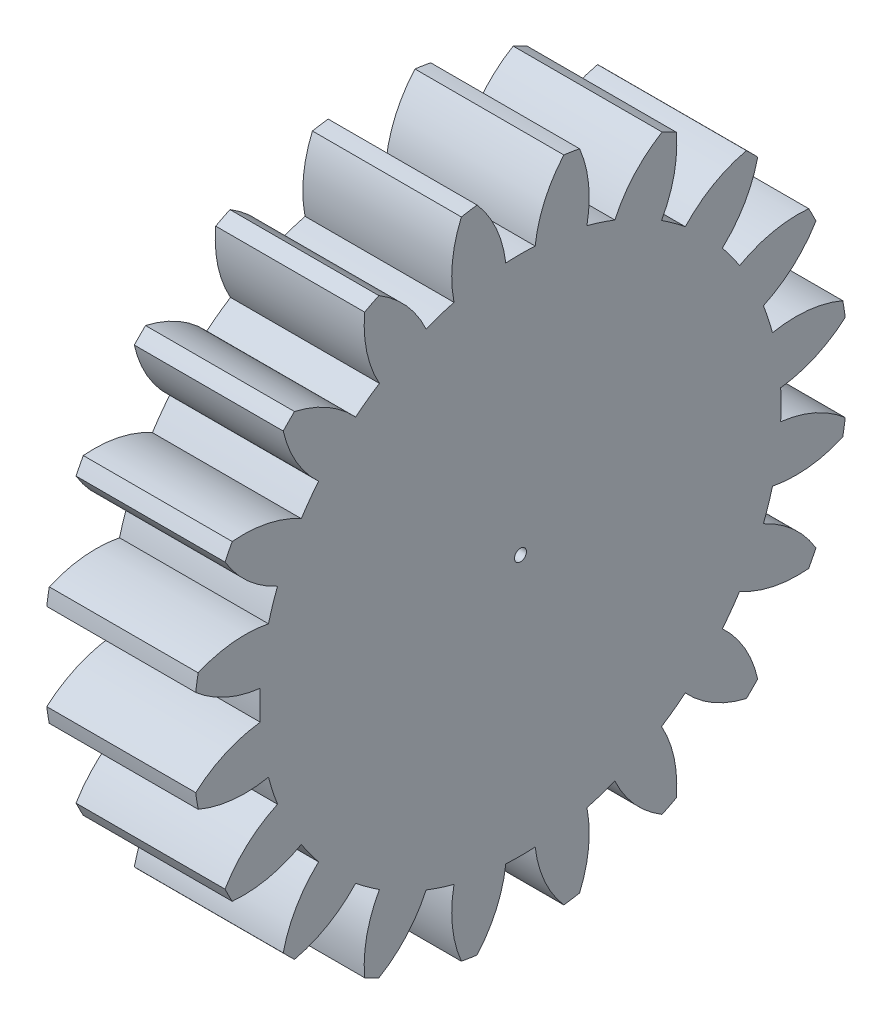
SolidWorks part; units mm, degrees
ref_plane "Plane1" through (0, 0, 0) normal (0, 0, 1) x (1, 0, 0)
ref_plane "Plane2" through (0, 0, 0) normal (0, 1, 0) x (1, 0, 0)
ref_plane "Plane3" through (0, 0, 0) normal (1, 0, 0) x (0, 0, -1)
sketch "HoldingSke" plane through (0, 0, 0) normal (0, 1, 0) x (1, 0, 0)
  line L0 (0, 0) -> (0.4698, -0.171)
  line L1 (-15, 0) -> (100, 0) construction
  line L2 (0, 0) -> (-2.1039, 2.3779)
  line L3 (0, 0) -> (-11.863, 4.5341)
  line L4 (0, 0) -> (8.1152, 2.9537)
  line L5 (0, 0) -> (-46.8476, -17.4728)
  line L6 (0, 0) -> (-9.9476, -6.7116)
  line L7 (-2.1039, 2.3779) -> (8.6586, 51.2059)
  line L8 (-76.2, 54.61) -> (-76.1, 54.61)
  line L9 (-71.009, 38.7566) -> (-53.1078, 45.2721)
  line L10 (-76.2, 71.12) -> (104.1128, 71.12)
  line L11 (0, 0) -> (-12, 0)
  line L12 (-76.2, 101.6) -> (-76.133, 101.6)
  line L13 (24.9733, 27.94) -> (52.9518, 28.4284)
  line L14 (24.9733, 27.94) -> (24.9743, 27.94)
  line L15 (24.9733, 27.94) -> (100.4006, 29.5858)
  line L16 (-63.627, -2) -> (-12.827, -2)
  circle A0 centre (0, 0) radius 0.4
  circle A1 centre (0, 0) radius 17.499
  circle A2 centre (0, 0) radius 37.5
  circle A3 centre (0, 0) radius 0.4
  dimension "MHD" = 34.998
  dimension "Hub_dia" = 75
  dimension "Bore" = 0.8
  dimension "MBD" = 0.8
  dimension "Num_teeth" = 20
  dimension "Pitch_radius" = 180.3128
  dimension "Pitch" = 0.5
  dimension "Width" = 12
  dimension "Overall_len" = 50
  dimension "Show_teeth" = 20
  dimension "Thickness" = 12
  dimension "OAL" = 50.0001
  dimension "T_dim" = 0.1
  dimension "Ap" = 20
  dimension "H" = 19.05
  dimension "Backlash" = 0.067
  dimension "Addendum_fac" = 1
  dimension "Dedendum_fac" = 1.25
  dimension "Clearance_fac" = 0.25
  dimension "Dedendum_add" = 0.001
  dimension "Module" = 2
sketch "BasProSke" plane through (0, 0, 0) normal (0, 1, 0) x (1, 0, 0)
  line L0 (-10, 0) -> (60, 0) construction
  line L1 (0, 0) -> (0, 22)
  line L2 (0, 0) -> (10, 0)
  line L3 (10, 0) -> (10, 22)
  line L4 (10, 22) -> (0, 22)
  dimension "Diameter" = 44
  dimension "Thickness" = 10
revolve "Base-Revolve" add sketch "BasProSke" angle 360 about L0
sketch "TooCutSke" plane through (0, 0, 0) normal (1, 0, 0) x (0, 0, -1)
  line L1 (0, 0) -> (0, 107) construction
  line L2 (0, 0) -> (-1.6864, 19.9288) construction
  line L3 (0, 0) -> (-6.2409, 39.4033) construction
  line L4 (-1.6864, 19.9288) -> (-3.1204, 19.7016) construction
  arc A0 (0.9862, 17.4712) -> (-0.9862, 17.4712) centre (0, 0) ccw
  arc A1 (2.9329, 21.8293) -> (-2.9329, 21.8293) centre (0, 0) ccw
  circle A2 centre (0, 0) radius 20 construction
  circle A3 centre (0, 0) radius 18.7939 construction
  arc A4 (-0.9862, 17.4712) -> (-2.9329, 21.8293) centre (-8.9313, 16.536) ccw
  arc A5 (2.9329, 21.8293) -> (0.9862, 17.4712) centre (8.9313, 16.536) ccw
  dimension "Root_dia" = 34.998
  dimension "Overcut_dia" = 44.0508
  dimension "Pitch_dia" = 40
  dimension "Base_dia" = 37.5877
  dimension "Flank_rad" = 8
  dimension "Half_ang" = 9
  dimension "Half_CT" = 1.4519
extrude "ToothCut" cut sketch "TooCutSke" along normal through all
fillet "Breaks" [suppressed] radius 0.04
fillet "RootFillets" [suppressed] radius 0.501
pattern_circular "TeethCuts" count 20 every 18 about axis through (-10, 0, 0) along (1, 0, 0) of "ToothCut", "RootFillets", "Breaks"
sketch "HubNeaOneSke" plane through (0, 0, 0) normal (-1, 0, 0) x (0, 0, 1)
  circle A0 centre (0, 0) radius 17.499
  dimension "Diameter" = 34.998
extrude "HubNearOne" [suppressed] add sketch "HubNeaOneSke" along normal blind 40.0001
sketch "HubNeaBotSke" plane through (0, 0, 0) normal (-1, 0, 0) x (0, 0, 1)
  circle A0 centre (0, 0) radius 17.499
  dimension "Diameter" = 34.998
extrude "HubNearBoth" [suppressed] add sketch "HubNeaBotSke" along normal blind 20
ref_plane "FarPln" through (10, 0, 0) normal (1, 0, 0) x (0, 0, -1)
sketch "HubFarSke" plane through (10, 0, 0) normal (1, 0, 0) x (0, 0, -1)
  circle A0 centre (0, 0) radius 17.499
  dimension "Diameter" = 34.998
extrude "HubFar" [suppressed] add sketch "HubFarSke" along normal blind 20
sketch "BorSke" plane through (0, 0, 0) normal (1, 0, 0) x (0, 0, -1)
  circle A0 centre (0, 0) radius 0.4
  dimension "Diameter" = 0.8
extrude "Bore" cut sketch "BorSke" along normal mid plane 100.0001
sketch "KeySke" plane through (0, 0, 0) normal (1, 0, 0) x (0, 0, -1)
  line L0 (-0.05, 0) -> (-0.05, 0.5)
  line L1 (-0.05, 0.5) -> (0.05, 0.5)
  line L2 (0.05, 0.5) -> (0.05, 0)
  line L3 (0, 0) -> (0, 34) construction
  line L4 (-0.05, 0) -> (0.05, 0)
  dimension "Offset" = 0.5
  dimension "Width" = 0.1
extrude "Keyway" [suppressed] cut sketch "KeySke" along normal mid plane 100.0001
pattern_circular "Keyway2" [suppressed] count 2 every 90 about axis through (-10, 0, 0) along (1, 0, 0)
equation "' \"Module@HoldingSke\" = 6.35"
equation "' \"Num_teeth@HoldingSke\" = 12"
equation "' \"Ap@HoldingSke\" =  20"
equation "' \"Width@HoldingSke\" = 0.5 * 25.4"
equation "' \"Hub_dia@HoldingSke\"= 1 * 25.4"
equation "' \"Overall_len@HoldingSke\" = 1.0 * 25.4"
equation "' \"Bore@HoldingSke\" = 0.75 * 25.4"
equation "' \"T_dim@HoldingSke\" = 0.1 * 25.4"
equation "' \"Width@KeySke\" = 0.25 * 25.4"
equation "' \"Show_teeth@HoldingSke\" = 13"
equation "' \"Backlash@HoldingSke\" = 0.009 * 25.4"
equation "' \"Addendum_fac@HoldingSke\" = 1.0"
equation "' \"Dedendum_fac@HoldingSke\" = 1.25"
equation "' \"Dedendum_add@HoldingSke\" = 0.00005 * 25.4"
equation "' \"Clearance_fac@HoldingSke\" = 0.25"
equation "\"Pitch@HoldingSke\" = 1 / \"Module@HoldingSke\""
equation "\"Overcut_dia@TooCutSke\" = (\"Num_teeth@HoldingSke\" + 2 * \"Addendum_fac@HoldingSke\") / \"Pitch@HoldingSke\" + 0.002 * 25.4"
equation "\"Pitch_dia@TooCutSke\" = \"Num_teeth@HoldingSke\" / \"Pitch@HoldingSke\""
equation "\"Base_dia@TooCutSke\" = \"Num_teeth@HoldingSke\" / \"Pitch@HoldingSke\" * cos((\"Ap@HoldingSke\"  * 3.14159265 / 180))"
equation "\"Root_dia@TooCutSke\" = (\"Num_teeth@HoldingSke\" + 2) / \"Pitch@HoldingSke\" - 2 * (\"Addendum_fac@HoldingSke\" + \"Dedendum_fac@HoldingSke\") / \"Pitch@HoldingSke\" - \"Dedendum_add@HoldingSke\" * 2"
equation "\"Half_ang@TooCutSke\" = 180 / \"Num_teeth@HoldingSke\""
equation "\"Half_CT@TooCutSke\" = \"Num_teeth@HoldingSke\" / \"Pitch@HoldingSke\" * sin((3.14159265 / 2 / \"Num_teeth@HoldingSke\")) / 2 - 7 * \"Backlash@HoldingSke\" / 4"
equation "\"Flank_rad@TooCutSke\" = \"Num_teeth@HoldingSke\" / \"Pitch@HoldingSke\" / 5"
equation "\"Radius@RootFillets\" = \"Clearance_fac@HoldingSke\" / \"Pitch@HoldingSke\" + \"Dedendum_add@HoldingSke\""
equation "\"Break_rad@Breaks\" = 0.02 / \"Pitch@HoldingSke\""
equation "\"Thickness@HoldingSke\" = \"Width@HoldingSke\""
equation "\"OAL@HoldingSke\" = \"Thickness@HoldingSke\""
equation "\"MHD@HoldingSke\" = (\"Num_teeth@HoldingSke\" + 2) / \"Pitch@HoldingSke\" - 2 * (\"Addendum_fac@HoldingSke\" + \"Dedendum_fac@HoldingSke\")  / \"Pitch@HoldingSke\" - \"Dedendum_add@HoldingSke\" * 2"
equation "\"MBD@HoldingSke\" = (\"Num_teeth@HoldingSke\" + 2) / \"Pitch@HoldingSke\" - 2 * (\"Addendum_fac@HoldingSke\" + \"Dedendum_fac@HoldingSke\")  / \"Pitch@HoldingSke\" - \"Dedendum_add@HoldingSke\" * 2 - 0.002 * 25.4"
equation "\"MHD@HoldingSke\" = ((sgn( \"MHD@HoldingSke\" - \"Hub_dia@HoldingSke\" )-1)*( \"MHD@HoldingSke\" - \"Hub_dia@HoldingSke\" ))/-2+ \"Hub_dia@HoldingSke\""
equation "\"MBD@HoldingSke\" = ((sgn( \"MBD@HoldingSke\" - \"Bore@HoldingSke\" )-1)*( \"MBD@HoldingSke\" - \"Bore@HoldingSke\" ))/-2+ \"Bore@HoldingSke\""
equation "\"OAL@HoldingSke\" = ((sgn( \"OAL@HoldingSke\" - \"Overall_len@HoldingSke\" )+1)*( \"OAL@HoldingSke\" - \"Overall_len@HoldingSke\" ))/2 + \"Overall_len@HoldingSke\" + 0.000002 * 25.4"
equation "\"Num_teeth@TeethCuts\" = int( \"Show_teeth@HoldingSke\" ) + 1"
equation "\"Num_teeth@TeethCuts\" = ((sgn( \"Num_teeth@TeethCuts\" - \"Num_teeth@HoldingSke\" )-1)*( \"Num_teeth@TeethCuts\" - \"Num_teeth@HoldingSke\" ))/-2+ \"Num_teeth@HoldingSke\""
equation "\"Num_teeth@TeethCuts\" = ((sgn( \"Num_teeth@TeethCuts\" - 2.0)+1)*( \"Num_teeth@TeethCuts\" - 2.0))/2 +2.0"
equation "\"Angle@TeethCuts\" = 360.0 / \"Num_teeth@HoldingSke\""
equation "\"Diameter@BasProSke\" = (\"Num_teeth@HoldingSke\" + 2 * \"Addendum_fac@HoldingSke\") / \"Pitch@HoldingSke\""
equation "' \"Fillet_rad@BasProSke\" =  \"Thickness@HoldingSke\" * 0.05"
equation "\"MHD@HoldingSke\" = ((sgn( \"MHD@HoldingSke\" - \"Root_dia@TooCutSke\" )-1)*( \"MHD@HoldingSke\" - \"Root_dia@TooCutSke\" ))/-2+ \"Root_dia@TooCutSke\""
equation "\"Diameter@HubNeaOneSke\" = \"MHD@HoldingSke\""
equation "\"Length@HubNearOne\" = \"OAL@HoldingSke\" - \"Thickness@BasProSke\""
equation "\"Diameter@HubNeaBotSke\" = \"MHD@HoldingSke\""
equation "\"Length@HubNearBoth\" = ( \"OAL@HoldingSke\" - \"Thickness@BasProSke\" ) / 2.0"
equation "\"Thickness@FarPln\" = \"Thickness@BasProSke\""
equation "\"Diameter@HubFarSke\" = \"MHD@HoldingSke\""
equation "\"Length@HubFar\" = ( \"OAL@HoldingSke\" - \"Thickness@BasProSke\" ) / 2.0"
equation "\"Diameter@BorSke\" = \"MBD@HoldingSke\""
equation "\"D1@Bore\" = \"OAL@HoldingSke\" * 2.0"
equation "\"D1@Keyway\" = \"OAL@HoldingSke\" * 2.0"
equation "\"Offset@KeySke\" = \"T_dim@HoldingSke\" + \"MBD@HoldingSke\" / 2.0"
